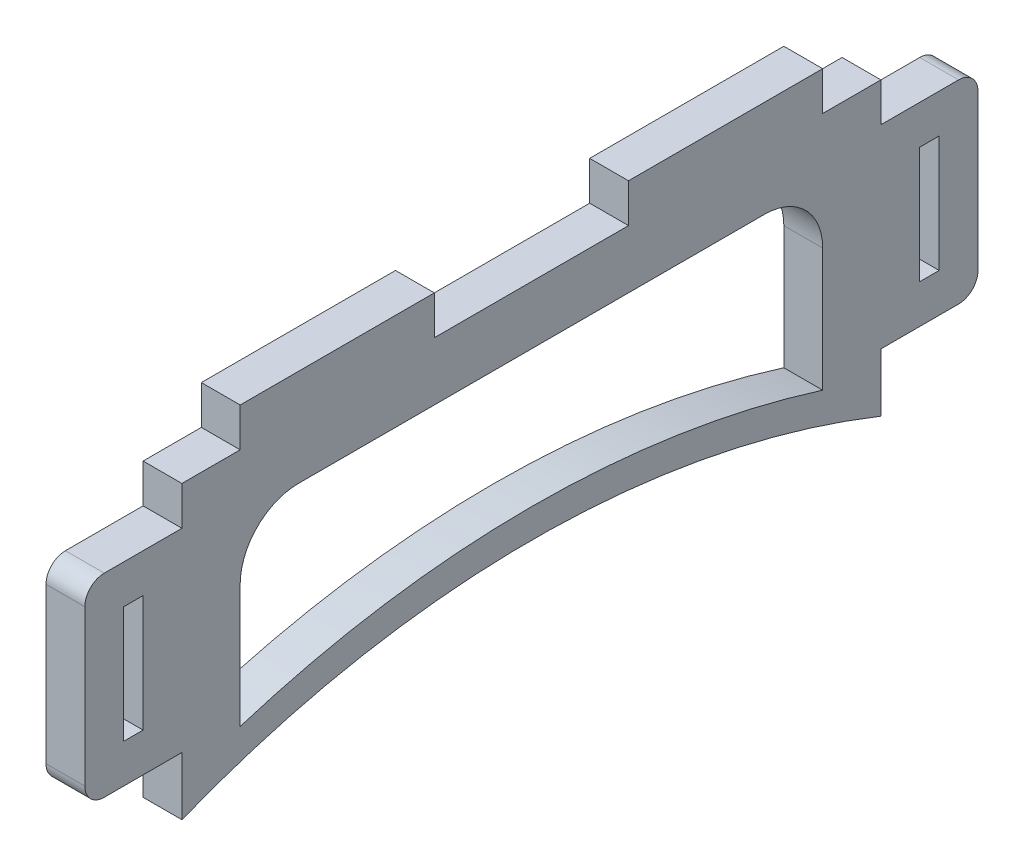
SolidWorks part; units mm, degrees
ref_plane "Front Plane" through (0, 0, 0) normal (0, 0, 1) x (1, 0, 0)
ref_plane "Top Plane" through (0, 0, 0) normal (0, 1, 0) x (1, 0, 0)
ref_plane "Right Plane" through (0, 0, 0) normal (1, 0, 0) x (0, 0, -1)
sketch "Sketch1" plane through (0, 0, 0) normal (1, 0, 0) x (0, 0, -1)
  line L0 (0, 10) -> (0, -167.3317) construction
  line L1 (-18, 0) -> (-15, 0)
  line L2 (-18, 0) -> (-18, -2)
  line L3 (-15, -12.3391) -> (-15, -6)
  line L4 (18, 0) -> (18, -2)
  line L5 (15, -6) -> (15, -12.3391)
  line L6 (-12, -3) -> (12, -3)
  line L7 (-5, 0) -> (5, 0)
  line L8 (5, 0) -> (5, 2)
  line L9 (-15, 0) -> (-15, 2)
  line L10 (-15, 2) -> (-5, 2)
  line L11 (-5, 0) -> (-5, 2)
  line L12 (15, 2) -> (5, 2)
  line L13 (15, 0) -> (15, 2)
  line L14 (15, 0) -> (18, 0)
  line L15 (-18, -2) -> (-22, -2)
  line L16 (-23, -3) -> (-23, -11)
  line L17 (-22, -12) -> (-18, -12)
  line L18 (-18, -12) -> (-18, -15)
  line L19 (18, -2) -> (22, -2)
  line L20 (23, -3) -> (23, -11)
  line L21 (22, -12) -> (18, -12)
  line L22 (18, -12) -> (18, -15)
  line L24 (-21, -4) -> (-20, -4)
  line L25 (-21, -4) -> (-21, -10)
  line L26 (-21, -10) -> (-20, -10)
  line L27 (-20, -4) -> (-20, -10)
  line L28 (20, -4) -> (21, -4)
  line L29 (20, -4) -> (20, -10)
  line L30 (20, -10) -> (21, -10)
  line L31 (21, -4) -> (21, -10)
  arc A0 (18, -15) -> (-18, -15) centre (0, -60.0361) ccw
  arc A1 (15, -12.3391) -> (-15, -12.3391) centre (0, -60.0361) ccw
  arc A2 (15, -6) -> (12, -3) centre (12, -6) ccw
  arc A3 (-12, -3) -> (-15, -6) centre (-12, -6) ccw
  arc A4 (-23, -11) -> (-22, -12) centre (-22, -11) ccw
  arc A5 (-22, -2) -> (-23, -3) centre (-22, -3) ccw
  arc A6 (23, -11) -> (22, -12) centre (22, -11) cw
  arc A7 (22, -2) -> (23, -3) centre (22, -3) cw
  dimension "D1" = 97
  dimension "D2" = 3
  dimension "D3" = 1
extrude "Boss-Extrude1" add sketch "Sketch1" along normal blind 2
